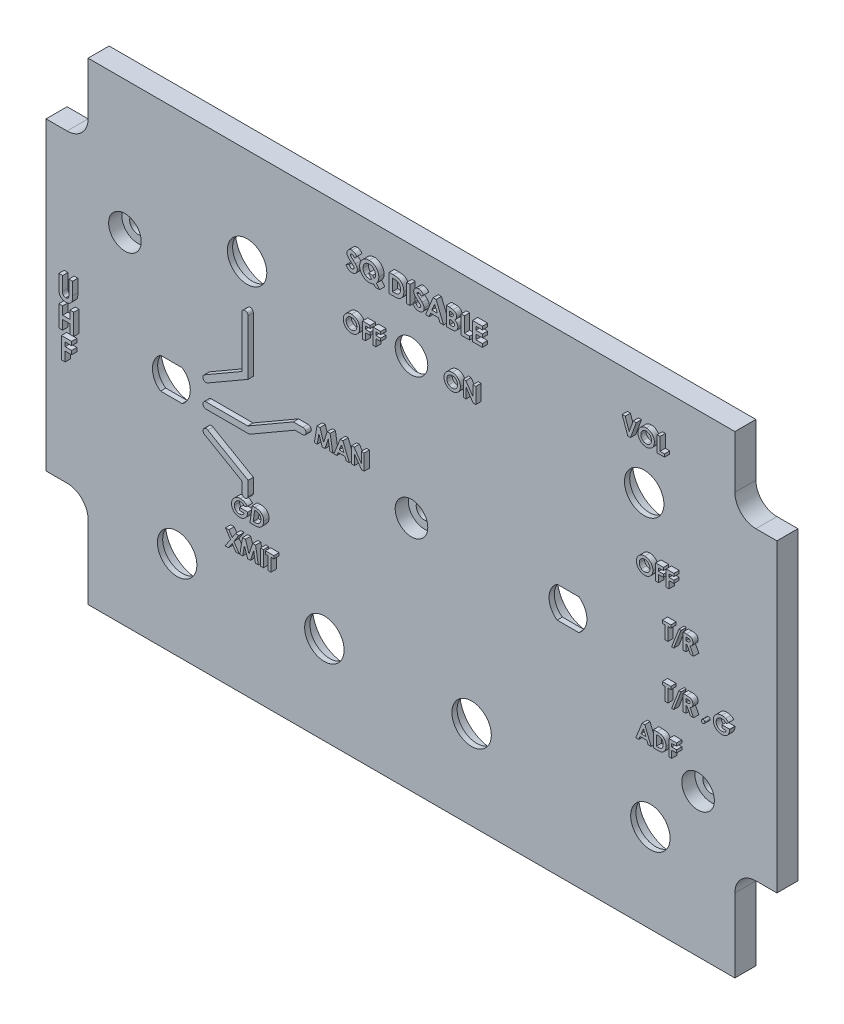
SolidWorks part; units mm, degrees
ref_plane "Front Plane" through (0, 0, 0) normal (0, 0, 1) x (1, 0, 0)
ref_plane "Top Plane" through (0, 0, 0) normal (0, 1, 0) x (1, 0, 0)
ref_plane "Right Plane" through (0, 0, 0) normal (1, 0, 0) x (0, 0, -1)
sketch "Sketch1" plane through (0, 0, 0) normal (0, 0, 1) x (1, 0, 0)
  line L1 (8, -0.3546) -> (131, -0.3546)
  line L2 (0, 17.6454) -> (0, 75.6454)
  line L3 (8, 89.6454) -> (131, 89.6454)
  line L4 (139, 17.6454) -> (139, 75.6454)
  line L5 (25.8954, 47.5954) -> (21.7686, 47.5954) construction
  line L6 (21.7686, 41.6954) -> (25.8954, 41.6954) construction
  line L11 (21.7686, 41.6954) -> (25.8954, 41.6954)
  line L12 (25.8954, 47.5954) -> (21.7686, 47.5954)
  line L13 (8, 89.6454) -> (8, 79.6454)
  line L14 (4, 75.6454) -> (0, 75.6454)
  line L15 (8, -0.3546) -> (8, 13.6454)
  line L16 (4, 17.6454) -> (0, 17.6454)
  line L17 (131, 89.6454) -> (131, 79.6454)
  line L18 (135, 75.6454) -> (139, 75.6454)
  line L19 (131, -0.3546) -> (131, 13.6454)
  line L20 (135, 17.6454) -> (139, 17.6454)
  line L23 (0, 0) -> (0, 87.0008) construction
  line L28 (97.1984, 41.6954) -> (101.3252, 41.6954)
  line L29 (101.3252, 47.5954) -> (97.1984, 47.5954)
  arc A8 (8, 13.6454) -> (4, 17.6454) centre (4, 13.6454) ccw
  arc A9 (8, 79.6454) -> (4, 75.6454) centre (4, 79.6454) cw
  arc A11 (131, 13.6454) -> (135, 17.6454) centre (135, 13.6454) cw
  arc A12 (131, 79.6454) -> (135, 75.6454) centre (135, 79.6454) ccw
  circle A13 centre (113.7516, 70.9208) radius 3.75 construction
  circle A14 centre (124, 26.8968) radius 1.6 construction
  circle A15 centre (114.932, 16.4873) radius 3.75 construction
  arc A16 (25.8954, 41.6954) -> (25.8954, 47.5954) centre (23.832, 44.6454) ccw construction
  circle A17 centre (80.932, 16.4873) radius 3.75 construction
  circle A18 centre (69.5, 71.3208) radius 3.1 construction
  circle A19 centre (38.2351, 71.2595) radius 3.75 construction
  circle A20 centre (52.932, 16.4873) radius 3.75 construction
  circle A21 centre (24.932, 16.4873) radius 3.75 construction
  circle A22 centre (15, 64.4595) radius 1.6 construction
  circle A24 centre (113.7516, 70.9208) radius 3.75
  circle A25 centre (124, 26.8968) radius 1.6
  circle A26 centre (114.932, 16.4873) radius 3.75
  circle A28 centre (80.932, 16.4873) radius 3.75
  circle A29 centre (69.5, 71.3208) radius 3.1
  circle A30 centre (38.2351, 71.2595) radius 3.75
  circle A31 centre (52.932, 16.4873) radius 3.75
  circle A32 centre (24.932, 16.4873) radius 3.75
  circle A33 centre (15, 64.4595) radius 1.6
  circle A35 centre (4, 13.1454) radius 1.6 construction
  circle A36 centre (4, 13.1454) radius 1.6 construction
  circle A38 centre (135, 13.1454) radius 1.6 construction
  circle A39 centre (135, 13.1454) radius 1.6 construction
  arc A41 (21.7686, 47.5954) -> (21.7686, 41.6954) centre (23.832, 44.6454) ccw construction
  arc A42 (21.7686, 47.5954) -> (21.7686, 41.6954) centre (23.832, 44.6454) ccw
  arc A43 (25.8954, 41.6954) -> (25.8954, 47.5954) centre (23.832, 44.6454) ccw
  arc A50 (101.3252, 41.6954) -> (101.3252, 47.5954) centre (99.2618, 44.6454) ccw
  arc A51 (97.1984, 47.5954) -> (97.1984, 41.6954) centre (99.2618, 44.6454) ccw
  circle A56 centre (69.5, 44.6454) radius 1.6 construction
  circle A57 centre (69.5, 44.6454) radius 1.6
  point P21 (131, 17.6454)
  point P25 (8, 75.6454)
  point P40 (131, 75.6454)
  dimension "D3" = 18
  dimension "D4" = 14
  dimension "D5" = 8
  dimension "D12" = 4
  dimension "D7" = 90
  dimension "D11" = 8
  dimension "D15" = 123
  dimension "D16" = 139
  dimension "D22" = 8
  dimension "D9" = 8
extrude "Boss-Extrude1" add sketch "Sketch1" along normal blind 4
sketch "Sketch5" plane through (0, 0, 0) normal (0, 0, -1) x (-1, 0, 0)
  circle A0 centre (-69.5, 71.3208) radius 3.1 construction
  circle A1 centre (-38.2351, 71.2595) radius 3.75 construction
  circle A3 centre (-24.932, 16.4873) radius 3.75 construction
  circle A4 centre (-52.932, 16.4873) radius 3.75 construction
  circle A5 centre (-80.932, 16.4873) radius 3.75 construction
  circle A6 centre (-114.932, 16.4873) radius 3.75 construction
  circle A8 centre (-113.7516, 70.9208) radius 3.75 construction
  circle A9 centre (-69.5, 71.3208) radius 3.1 construction
  circle A10 centre (-38.2351, 71.2595) radius 3.75 construction
  circle A12 centre (-24.932, 16.4873) radius 3.75 construction
  circle A13 centre (-52.932, 16.4873) radius 3.75 construction
  circle A14 centre (-80.932, 16.4873) radius 3.75 construction
  circle A15 centre (-114.932, 16.4873) radius 3.75 construction
  circle A17 centre (-113.7516, 70.9208) radius 3.75 construction
  circle A18 centre (-69.5, 71.3208) radius 6.7
  circle A19 centre (-38.2351, 71.2595) radius 6.25
  circle A21 centre (-24.932, 16.4873) radius 6.25
  circle A22 centre (-52.932, 16.4873) radius 6.25
  circle A23 centre (-80.932, 16.4873) radius 6.25
  circle A24 centre (-114.932, 16.4873) radius 6.25
  circle A26 centre (-113.7516, 70.9208) radius 6.25
  arc A27 (-25.8954, 47.5954) -> (-25.8954, 41.6954) centre (-23.832, 44.6454) ccw construction
  circle A29 centre (-23.832, 44.6454) radius 3.6 construction
  arc A30 (-101.3252, 47.5954) -> (-101.3252, 41.6954) centre (-99.2618, 44.6454) ccw construction
  circle A31 centre (-23.832, 44.6454) radius 6
  circle A33 centre (-99.2618, 44.6454) radius 3.6 construction
  circle A34 centre (-99.2618, 44.6454) radius 6
  point P0 (0, 0)
  point P6 (0, 0)
  point P8 (0, 0)
  point P10 (0, 0)
  point P12 (0, 0)
  point P16 (-113.7516, 70.9208)
  point P31 (0, 0)
  point P42 (0, 0)
  dimension "D3" = 2.4
  dimension "D1" = 13.4
  dimension "D4" = 12.5
  dimension "D5" = 12
  dimension "D6" = 12
  dimension "D2" = 2.4
extrude "Back holes" cut sketch "Sketch5" against normal blind 3
sketch "Sketch6" plane through (0, 0, 4) normal (0, 0, 1) x (1, 0, 0)
  circle A0 centre (15, 64.4595) radius 1.6 construction
  circle A1 centre (124, 26.8968) radius 1.6 construction
  circle A2 centre (15, 64.4595) radius 1.6 construction
  circle A3 centre (124, 26.8968) radius 1.6 construction
  circle A4 centre (124, 26.8968) radius 3.1
  circle A5 centre (15, 64.4595) radius 3.1
  circle A7 centre (69.5, 44.6454) radius 3.1
  dimension "D1" = 1.5
extrude "Cama tornillos" cut sketch "Sketch6" against normal blind 2.5
sketch "Sketch4" plane through (0, 0, 4) normal (0, 0, 1) x (1, 0, 0)
  line L0 (6.0227, 54.5551) -> (6.0227, 14.5758) construction
  line L3 (23.832, 44.6454) -> (30.219, 40.9578) construction
  line L4 (-3.2263, 48.4268) -> (14.9404, 48.4268) construction
  line L5 (-3.2263, 43.4268) -> (14.9404, 43.4268) construction
  line L6 (-3.2263, 38.4268) -> (14.9404, 38.4268) construction
  line L7 (3.0227, 54.5551) -> (3.0227, 14.5758) construction
  line L8 (23.832, 44.6454) -> (45.3148, 57.0485) construction
  line L9 (8, -0.3546) -> (131, -0.3546) construction
  line L10 (31.4349, 49.0349) -> (38.8294, 53.3041) construction
  line L11 (38.8294, 53.3041) -> (38.8294, 63.4187) construction
  line L12 (31.1349, 49.5545) -> (38.2294, 53.6505)
  line L13 (38.2294, 53.6505) -> (38.2294, 63.4187)
  line L14 (31.7349, 48.5153) -> (39.4294, 52.9577)
  line L15 (39.4294, 52.9577) -> (39.4294, 63.4187)
  line L16 (31.4483, 44.6454) -> (39.5208, 44.6454) construction
  line L17 (39.5208, 44.6454) -> (48.1811, 49.6454) construction
  line L18 (48.1811, 49.6454) -> (49.8455, 49.6454) construction
  line L19 (31.4483, 44.0454) -> (39.6816, 44.0454)
  line L20 (39.6816, 44.0454) -> (48.3419, 49.0454)
  line L21 (48.3419, 49.0454) -> (49.8455, 49.0454)
  line L22 (31.4483, 45.2454) -> (39.3601, 45.2454)
  line L23 (39.3601, 45.2454) -> (48.0203, 50.2454)
  line L24 (48.0203, 50.2454) -> (49.8455, 50.2454)
  line L25 (31.4531, 40.2453) -> (38.8294, 35.9866) construction
  line L26 (38.8294, 35.9866) -> (38.8294, 33.7296) construction
  line L27 (31.1531, 39.7257) -> (38.2294, 35.6402)
  line L28 (38.2294, 35.6402) -> (38.2294, 33.7296)
  line L29 (31.7531, 40.7649) -> (39.4294, 36.333)
  line L30 (39.4294, 36.333) -> (39.4294, 33.7296)
  line L31 (93.4618, 44.6454) -> (113.76, 44.6454) construction
  line L32 (99.2618, 44.6454) -> (113.1, 58.4836) construction
  line L33 (99.2618, 44.6454) -> (118.1651, 49.7105) construction
  line L34 (99.2618, 44.6454) -> (113.1, 30.8071) construction
  line L35 (99.2618, 44.6454) -> (118.1651, 39.5802) construction
  arc A0 (31.1349, 49.5545) -> (31.7349, 48.5153) centre (31.4349, 49.0349) ccw
  arc A1 (38.2294, 63.4187) -> (39.4294, 63.4187) centre (38.8294, 63.4187) cw
  arc A2 (31.4483, 44.0454) -> (31.4483, 45.2454) centre (31.4483, 44.6454) cw
  arc A3 (49.8455, 49.0454) -> (49.8455, 50.2454) centre (49.8455, 49.6454) ccw
  arc A4 (31.1531, 39.7257) -> (31.7531, 40.7649) centre (31.4531, 40.2453) cw
  arc A5 (38.2294, 33.7296) -> (39.4294, 33.7296) centre (38.8294, 33.7296) ccw
  arc A6 (21.7686, 47.5954) -> (21.7686, 41.6954) centre (23.832, 44.6454) ccw construction
  arc A7 (21.7686, 47.5954) -> (21.7686, 41.6954) centre (23.832, 44.6454) ccw construction
  arc A9 (97.1984, 47.5954) -> (97.1984, 41.6954) centre (99.2618, 44.6454) ccw construction
  arc A10 (97.1984, 47.5954) -> (97.1984, 41.6954) centre (99.2618, 44.6454) ccw construction
  text T0 "U" font "Century Gothic" height 4
  text T1 "<b>OFF</b>" font "Century Gothic" height 3
  text T2 "<b><i> GD</i></b>\r\n<b>XMIT</b>" font "Century Gothic" height 3
  text T3 "<b>MAN</b>" font "Century Gothic" height 3
  text T4 "<b>VOL</b>" font "Century Gothic" height 3
  text T7 "<b>ON</b>" font "Century Gothic" height 3
  text T8 "<b>SQ DISABLE</b>" font "Century Gothic" height 3.5
  text T9 "H" font "Century Gothic" height 4
  text T10 "F" font "Century Gothic" height 4
  text T11 "<b>OFF</b>" font "Century Gothic" height 3
  text T12 "<b>T/R</b>" font "Century Gothic" height 3
  text T13 "<b>T/R . G</b>" font "Century Gothic" height 3
  text T14 "<b>ADF</b>" font "Century Gothic" height 3
  dimension "D1" = 3
  dimension "D2" = 5
  dimension "D3" = 5
  dimension "D4" = 30
  dimension "D7" = 150
  dimension "D8" = 5
  dimension "D11" = 30
  dimension "D12" = 0.6
  dimension "D14" = 15
  dimension "D15" = 30
  dimension "D16" = 15
  dimension "D17" = 30
  dimension "D5" = 0.6
  dimension "D6" = 0.6
  dimension "D9" = 0.6
  dimension "D10" = 0.6
  dimension "D13" = 0.6
extrude "Textos" add sketch "Sketch4" along normal blind 1
